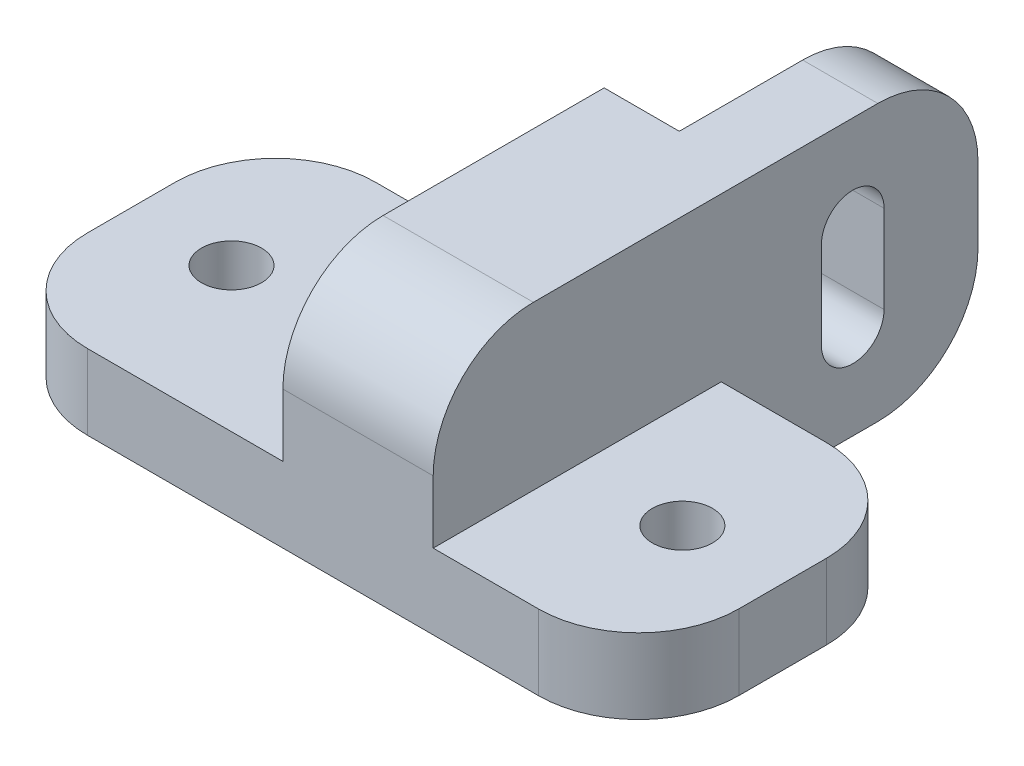
SolidWorks part; units mm, degrees
ref_plane "Front Plane" through (0, 0, 0) normal (0, 0, 1) x (1, 0, 0)
ref_plane "Top Plane" through (0, 0, 0) normal (0, 1, 0) x (1, 0, 0)
ref_plane "Right Plane" through (0, 0, 0) normal (1, 0, 0) x (0, 0, -1)
sketch "Sketch1" plane through (0, 0, 0) normal (0, 1, 0) x (1, 0, 0)
  line L1 (-13, -5.75) -> (13, -5.75)
  line L2 (-13, -5.75) -> (-13, 5.75)
  line L3 (-13, 5.75) -> (13, 5.75)
  line L4 (13, -5.75) -> (13, 5.75)
  line L5 (-13, -5.75) -> (13, 5.75) construction
  line L6 (-13, 5.75) -> (13, -5.75) construction
  point P0 (0, 0)
  dimension "D1" = 11.5
  dimension "D2" = 26
extrude "Boss-Extrude1" add sketch "Sketch1" along normal blind 3
fillet "Fillet1" radius 4 4 edges at (-13, 1.5, 5.75) (-13, 1.5, -5.75) (13, 1.5, -5.75) (13, 1.5, 5.75)
ref_plane "Plane1" through (1.8, 0, 0) normal (1, 0, 0) x (0, 0, -1)
sketch "Sketch2" plane through (1.8, 0, 0) normal (1, 0, 0) x (0, 0, -1)
  line L0 (-1.75, 3) -> (1.75, 3) construction
  line L1 (0, 3) -> (5.75, 3)
  line L2 (0, 3) -> (0, 9.5) construction
  line L3 (0, 9.5) -> (16, 9.5)
  line L4 (16, 3) -> (16, 9.5)
  line L5 (5.75, -1.5) -> (16, -1.5)
  line L6 (16, 3) -> (16, -1.5)
  line L7 (5.75, -1.5) -> (5.75, 3)
  line L8 (0, 9.5) -> (-5.75, 9.5)
  line L9 (-5.75, 3) -> (-5.75, 9.5)
  line L10 (-5.75, 3) -> (0, 3)
  line L11 (1.75, 0) -> (5.75, 0) construction
  dimension "D1" = 16
  dimension "D2" = 6.5
  dimension "D3" = 1.5
extrude "Boss-Extrude2" add sketch "Sketch2" along normal blind 3
fillet "Fillet2" radius 4 1 edges at (3.3, 9.5, 5.75)
sketch "Sketch4" plane through (1.8, 0, 0) normal (-1, 0, 0) x (0, 0, 1)
  line L1 (-7.075, 9.5) -> (-7.075, -1.5)
  line L8 (5.75, 3) -> (5.75, 5.5)
  line L9 (1.75, 9.5) -> (-16, 9.5)
  line L10 (-16, 9.5) -> (-16, -1.5)
  line L11 (-16, -1.5) -> (-5.75, -1.5)
  line L12 (-5.75, 0) -> (-5.75, 3)
  line L13 (-5.75, 3) -> (5.75, 3)
  line L14 (5.75, 3) -> (5.75, 5.5)
  line L15 (1.75, 9.5) -> (-7.075, 9.5)
  line L17 (-7.075, -1.5) -> (-5.75, -1.5)
  line L18 (-5.75, 0) -> (-5.75, 3)
  line L19 (-5.75, 3) -> (5.75, 3)
  line L20 (-5.75, -1.5) -> (-5.75, 0)
  line L21 (-5.75, -1.5) -> (-5.75, 0)
  arc A1 (5.75, 5.5) -> (1.75, 9.5) centre (1.75, 5.5) ccw
  arc A2 (5.75, 5.5) -> (1.75, 9.5) centre (1.75, 5.5) ccw
  dimension "D1" = 0
extrude "Boss-Extrude3" add sketch "Sketch4" along normal blind 3
sketch "Sketch3" plane through (4.8, 0, 0) normal (1, 0, 0) x (0, 0, -1)
  line L0 (16, 4) -> (5.75, 4) construction
  line L2 (5.75, 3) -> (5.75, 4) construction
  line L3 (16, -1.5) -> (16, 9.5) construction
  line L4 (11, 2.25) -> (11, 5.75) construction
  line L5 (9.75, 2.25) -> (9.75, 5.75)
  line L6 (12.25, 2.25) -> (12.25, 5.75)
  circle A0 centre (11, 4) radius 2.25 construction
  circle A1 centre (11, 4) radius 1.25 construction
  arc A2 (9.75, 2.25) -> (12.25, 2.25) centre (11, 2.25) ccw
  arc A3 (12.25, 5.75) -> (9.75, 5.75) centre (11, 5.75) ccw
  point P8 (11, 4)
  dimension "D1" = 5
extrude "Cut-Extrude2" cut sketch "Sketch3" against normal blind 4
fillet "Fillet3" radius 4 2 edges at (3.3, -1.5, -16) (3.3, 9.5, -16)
sketch "Sketch5" plane through (0, 0, 0) normal (0, -1, 0) x (1, 0, 0)
  circle A2 centre (8.998, -0.0006) radius 1.2
  circle A3 centre (-9.0001, 0.0011) radius 1.2
  dimension "D1" = 2.4
extrude "Cut-Extrude3" cut sketch "Sketch5" against normal blind 4
